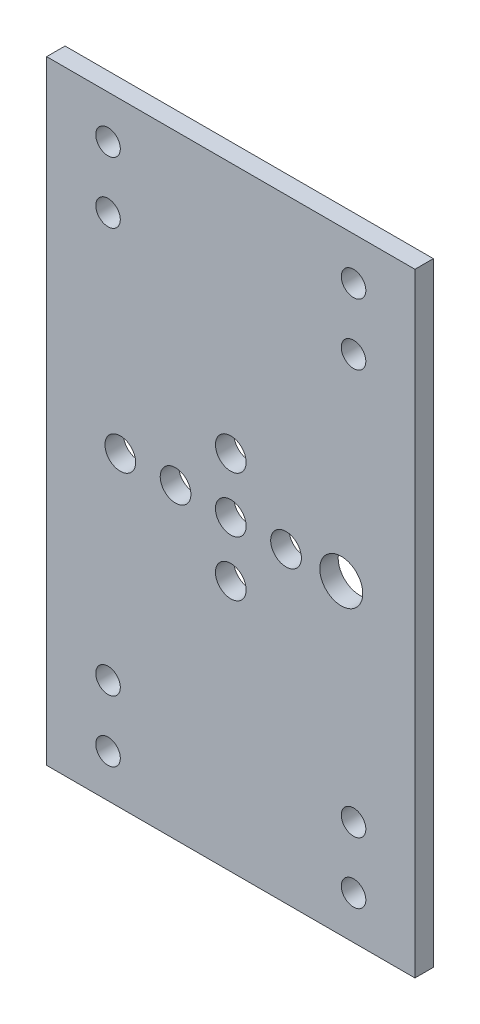
SolidWorks part; units mm, degrees
ref_plane "Спереди" through (0, 0, 0) normal (0, 0, 1) x (1, 0, 0)
ref_plane "Сверху" through (0, 0, 0) normal (0, 1, 0) x (1, 0, 0)
ref_plane "Справа" through (0, 0, 0) normal (1, 0, 0) x (0, 0, -1)
sketch "Эскиз1" plane through (0, 0, 0) normal (0, 0, 1) x (1, 0, 0)
  line L5 (0, 0) -> (-60, 0)
  line L6 (0, 0) -> (0, 100)
  line L7 (0, 100) -> (-60, 100)
  line L8 (-60, 0) -> (-60, 100)
  line L10 (-30, 50) -> (-60, 50) construction
  line L11 (-60, 50) -> (0, 50) construction
  line L12 (-30, 50) -> (-30, 100) construction
  line L13 (-30, 50) -> (-30, 0) construction
  circle A0 centre (-30, 50) radius 2.5
  circle A1 centre (-21, 50) radius 2.5
  circle A2 centre (-39, 50) radius 2.5
  circle A3 centre (-30, 41) radius 2.5
  circle A4 centre (-30, 59) radius 2.5
  circle A5 centre (-50, 93) radius 2
  circle A6 centre (-50, 83) radius 2
  circle A7 centre (-10, 83) radius 2
  circle A8 centre (-10, 93) radius 2
  circle A9 centre (-10, 17) radius 2
  circle A10 centre (-10, 7) radius 2
  circle A11 centre (-50, 7) radius 2
  circle A12 centre (-50, 17) radius 2
  circle A13 centre (-48, 50) radius 2.5
  circle A14 centre (-12, 50) radius 3.5
  dimension "D3" = 5
  dimension "D4" = 5
  dimension "D6" = 5
  dimension "D8" = 4
  dimension "D10" = 4
  dimension "D14" = 5
  dimension "D16" = 7
  dimension "D1" = 100
  dimension "D2" = 60
  dimension "D5" = 9
  dimension "D7" = 9
  dimension "D9" = 10
  dimension "D11" = 7
  dimension "D12" = 10
  dimension "D13" = 10
  dimension "D15" = 9
  dimension "D17" = 9
extrude "Бобышка-Вытянуть1" add sketch "Эскиз1" along normal blind 3
